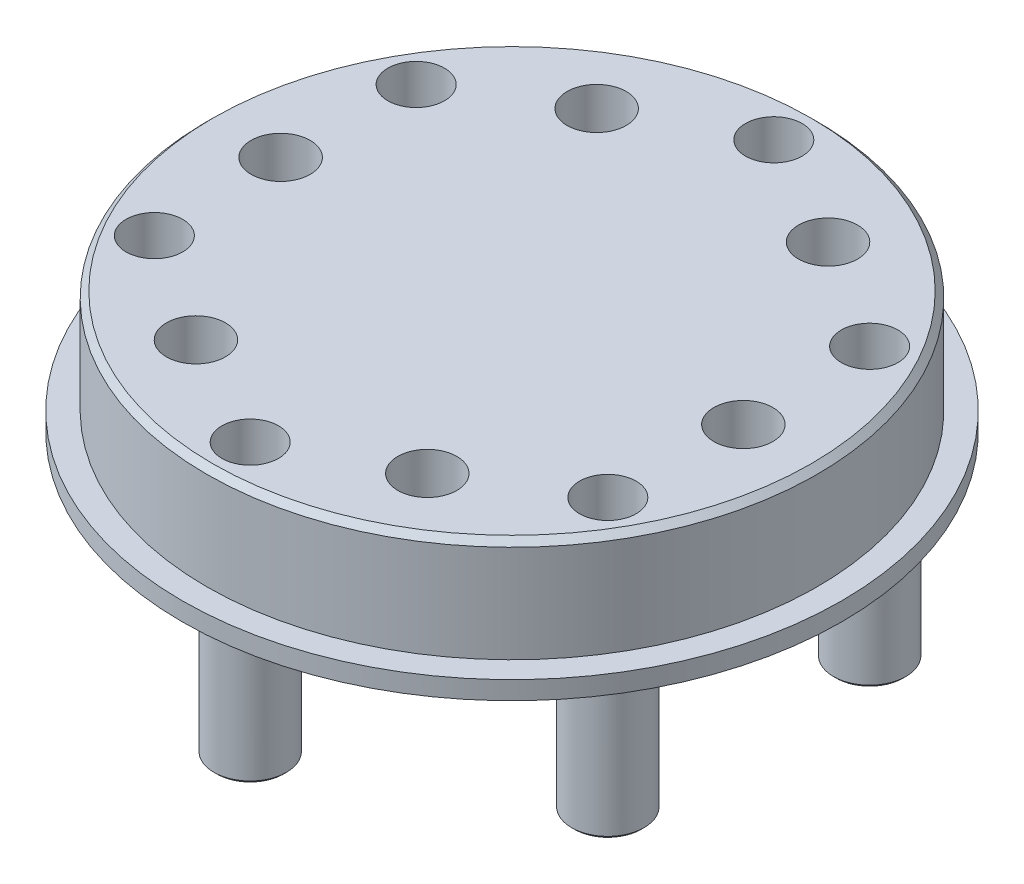
SolidWorks part; units mm, degrees
material "PLA"
ref_plane "Front Plane" through (0, 0, 0) normal (0, 0, 1) x (1, 0, 0)
ref_plane "Top Plane" through (0, 0, 0) normal (0, 1, 0) x (1, 0, 0)
ref_plane "Right Plane" through (0, 0, 0) normal (1, 0, 0) x (0, 0, -1)
sketch "Sketch2" plane through (0, 0, 0) normal (0, 1, 0) x (1, 0, 0)
  circle A0 centre (0, 0) radius 25.075
  circle A1 centre (0, 0) radius 21.5 construction
  circle A3 centre (0, 21.5) radius 1.35
  circle A4 centre (18.6195, 10.75) radius 1.35
  circle A5 centre (18.6195, -10.75) radius 1.35
  circle A6 centre (0, -21.5) radius 1.35
  circle A7 centre (-18.6195, -10.75) radius 1.35
  circle A8 centre (-18.6195, 10.75) radius 1.35
  circle A9 centre (0, 0) radius 11.025
  dimension "D1" = 50.15
  dimension "D2" = 43
  dimension "D3" = 2.7
  dimension "D5" = 22.05
  dimension "D4" = 6
extrude "Boss-Extrude1" add sketch "Sketch2" along normal blind 10
sketch "Sketch3" plane through (0, 10, 0) normal (0, 1, 0) x (1, 0, 0)
  circle A0 centre (0, 21.5) radius 2.325
  circle A4 centre (0, 0) radius 21.5 construction
  circle A5 centre (18.6195, 10.75) radius 2.325
  circle A6 centre (18.6195, -10.75) radius 2.325
  circle A7 centre (0, -21.5) radius 2.325
  circle A8 centre (-18.6195, -10.75) radius 2.325
  circle A9 centre (-18.6195, 10.75) radius 2.325
  circle M2 centre (-18.6195, -10.75) radius 1.35
  circle M3 centre (18.6195, -10.75) radius 1.35
  circle M6 centre (0, 21.5) radius 1.35
  circle M7 centre (18.6195, 10.75) radius 1.35
  circle M8 centre (0, -21.5) radius 1.35
  circle M9 centre (-18.6195, 10.75) radius 1.35
  dimension "D1" = 4.65
  dimension "D3" = 6
  dimension "D2" = 43
extrude "Cut-Extrude2" cut sketch "Sketch3" against normal offset from surface (5.75 mm away) 4.25 contours A0 M6 | M8 M3 | M9 M2 | A9 M9 | A5 M7 | A7 M8
sketch "Sketch11" plane through (0, 0, 0) normal (0, 1, 0) x (1, 0, 0)
  circle A0 centre (0, 0) radius 25.075
  circle A1 centre (0, 0) radius 27.075
  circle A3 centre (0, 0) radius 25.075 construction
  dimension "D2" = 54.15
  dimension "D1" = 2
extrude "Boss-Extrude6" add sketch "Sketch11" along normal blind 1.5
ref_plane "Plane1" through (0, 7, 0) normal (0, -1, 0) x (-1, 0, 0)
sketch "Sketch12" plane through (0, 7, 0) normal (0, 1, 0) x (1, 0, 0)
  circle A1 centre (0, 0) radius 10.025
  circle A2 centre (0, 0) radius 11.025 construction
  circle A3 centre (0, 0) radius 11.025
  dimension "D2" = 20.05
  dimension "D1" = 1
extrude "Boss-Extrude7" add sketch "Sketch12" along normal blind 1.5
sketch "Sketch13" plane through (0, 10, 0) normal (0, 1, 0) x (1, 0, 0)
  line L1 (0, 0) -> (0, 19) construction
  line L6 (0, 0) -> (-12.5, 21.6506) construction
  circle A0 centre (0, 0) radius 25 construction
  circle A4 centre (-9.5, 16.4545) radius 2.425
  circle A5 centre (0, 0) radius 19 construction
  dimension "D4" = 4.85
  dimension "D3" = 50
  dimension "D2" = 38
  dimension "D1" = 30
extrude "Cut-Extrude7" cut sketch "Sketch13" against normal blind 6
pattern_circular "CirPattern4" count 6 over 360 about axis through (0, 0, 0) along (0, 1, 0) of "Cut-Extrude7"
sketch "Sketch16" plane through (0, 0, 0) normal (0, -1, 0) x (1, 0, 0)
  circle A0 centre (0, 21.5) radius 1.35 construction
  circle A1 centre (0, -21.5) radius 2.975
  circle A2 centre (18.6195, -10.75) radius 1.35 construction
  circle A3 centre (-18.6195, -10.75) radius 2.975
  circle A4 centre (-18.6195, -10.75) radius 1.35 construction
  circle A5 centre (-18.6195, 10.75) radius 2.975
  circle A6 centre (0, 21.5) radius 1.35
  circle A8 centre (18.6195, -10.75) radius 1.35
  circle A10 centre (-18.6195, -10.75) radius 1.35
  circle A12 centre (0, 21.5) radius 2.975
  circle A13 centre (0, 0) radius 21.5 construction
  circle A14 centre (18.6195, 10.75) radius 2.975
  circle A15 centre (18.6195, -10.75) radius 2.975
  circle A16 centre (18.6195, 10.75) radius 1.35 construction
  circle A17 centre (0, -21.5) radius 1.35 construction
  circle A18 centre (-18.6195, 10.75) radius 1.35 construction
  circle A19 centre (18.6195, 10.75) radius 1.35
  circle A20 centre (0, -21.5) radius 1.35
  circle A21 centre (-18.6195, 10.75) radius 1.35
  dimension "D1" = 5.95
  dimension "D2" = 6
extrude "Boss-Extrude8" add sketch "Sketch16" along normal blind 12.25
sketch "Sketch17" plane through (0, 8.5, 0) normal (0, 1, 0) x (1, 0, 0)
  circle A0 centre (0, 0) radius 10.025 construction
  circle A1 centre (0, 0) radius 11.025
  circle A2 centre (0, 0) radius 11.025
  circle A3 centre (0, 0) radius 10.025
  dimension "D1" = 0
extrude "Boss-Extrude9" add sketch "Sketch17" along normal up to surface (1.5 mm away) up to face at (7.3999, 10, -15.242)
sketch "Sketch18" plane through (0, 10, 0) normal (0, 1, 0) x (1, 0, 0)
  circle A0 centre (0, 0) radius 10.025 construction
  circle A1 centre (0, 0) radius 10.025
chamfer "Chamfer1" distance 0.25 angle 45 6 edges at (18.6195, -12.25, 7.775) (0, -12.25, 18.525) (18.6195, -12.25, -13.725) (0, -12.25, -24.475) (-18.6195, -12.25, -13.725) (-18.6195, -12.25, 7.775)
chamfer "Chamfer2" distance 0.5 angle 45 2 edges at (0, 10, 25.075) (0, 0, 11.025)
extrude "Boss-Extrude10" add sketch "Sketch18" against normal blind 2
equation "\"M3 Heat Insert\"= 4.85mm"
equation "\"D4@Sketch13\"=\"M3 Heat Insert\""
